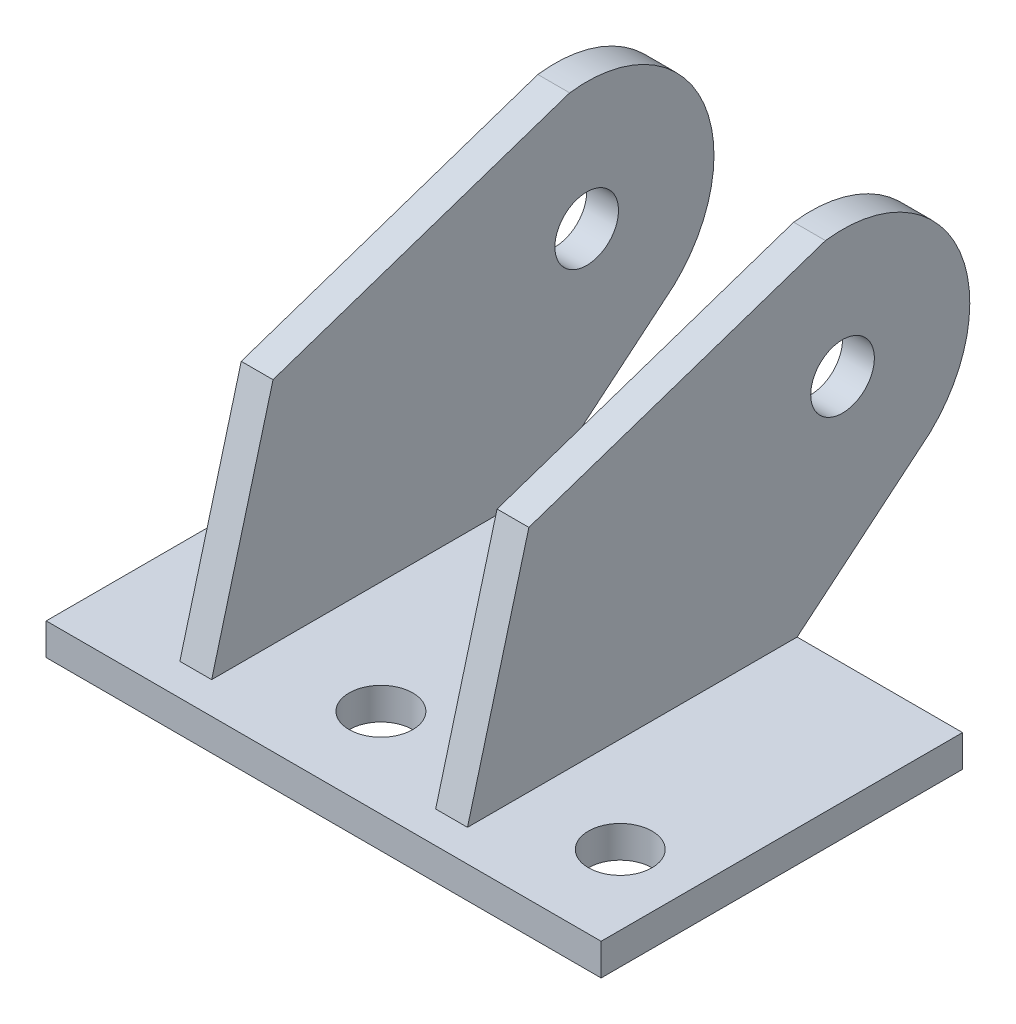
SolidWorks part; units mm, degrees
material "AISI 4130 Steel, annealed at 865C"
ref_plane "Front Plane" through (0, 0, 0) normal (0, 0, 1) x (1, 0, 0)
ref_plane "Top Plane" through (0, 0, 0) normal (0, 1, 0) x (1, 0, 0)
ref_plane "Right Plane" through (0, 0, 0) normal (1, 0, 0) x (0, 0, -1)
sketch "Sketch1" plane through (0, 0, 0) normal (0, 1, 0) x (1, 0, 0)
  line L1 (0, 0) -> (55.372, 0)
  line L2 (0, 0) -> (0, 36.068)
  line L3 (0, 36.068) -> (55.372, 36.068)
  line L4 (55.372, 0) -> (55.372, 36.068)
  line L5 (10.16, 29.718) -> (13.335, 29.718) construction
  line L6 (10.16, 29.718) -> (10.16, 10.414) construction
  line L7 (10.16, 10.414) -> (13.335, 10.414) construction
  line L8 (13.335, 29.718) -> (13.335, 10.414) construction
  line L9 (35.687, 29.718) -> (38.862, 29.718) construction
  line L10 (35.687, 29.718) -> (35.687, 10.414) construction
  line L11 (35.687, 10.414) -> (38.862, 10.414) construction
  line L12 (38.862, 29.718) -> (38.862, 10.414) construction
  circle A0 centre (24.511, 8.89) radius 3.175
  circle A1 centre (24.511, 26.162) radius 3.175
  circle A2 centre (48.387, 8.89) radius 3.175
  dimension "D12" = 6.35
  dimension "D13" = 6.35
  dimension "D14" = 6.35
  dimension "D1" = 55.372
  dimension "D2" = 36.068
  dimension "D3" = 10.16
  dimension "D4" = 6.35
  dimension "D5" = 3.175
  dimension "D6" = 19.304
  dimension "D7" = 22.352
  dimension "D8" = 3.175
  dimension "D9" = 19.304
  dimension "D10" = 11.176
  dimension "D11" = 11.176
  dimension "D15" = 8.89
  dimension "D16" = 17.272
  dimension "D17" = 23.876
extrude "Boss-Extrude1" add sketch "Sketch1" along normal blind 3.175
sketch "Sketch2" plane through (0, 3.175, 0) normal (0, 1, 0) x (1, 0, 0)
  line L0 (0, 0) -> (55.372, 0) construction
  line L1 (10.16, 3.175) -> (13.335, 3.175)
  line L2 (10.16, 3.175) -> (10.16, 53.975)
  line L3 (10.16, 53.975) -> (13.335, 53.975)
  line L4 (13.335, 3.175) -> (13.335, 53.975)
  line L5 (35.687, 3.175) -> (38.862, 3.175)
  line L6 (35.687, 3.175) -> (35.687, 53.975)
  line L7 (35.687, 53.975) -> (38.862, 53.975)
  line L8 (38.862, 3.175) -> (38.862, 53.975)
  circle A1 centre (24.511, 8.89) radius 3.175 construction
  dimension "D5" = 11.176
  dimension "D1" = 22.352
  dimension "D2" = 3.175
  dimension "D3" = 3.175
  dimension "D4" = 50.8
  dimension "D6" = 3.175
extrude "Boss-Extrude2" add sketch "Sketch2" along normal blind 38.1
sketch "Sketch3" plane through (10.16, 0, 0) normal (-1, 0, 0) x (0, 0, 1)
  circle A0 centre (-40.5975, 23.4355) radius 3.175
  dimension "D1" = 6.35
extrude "Cut-Extrude1" cut sketch "Sketch3" against normal up to surface (28.702 mm away) up to face at (38.862, 18.415, -30.0736)
sketch "Sketch4" plane through (10.16, 0, 0) normal (-1, 0, 0) x (0, 0, 1)
  line L0 (-3.175, 3.175) -> (-3.175, 41.275)
  line L1 (-3.175, 41.275) -> (-53.975, 41.275)
  line L2 (-53.975, 41.275) -> (-53.975, 3.175)
  line L3 (-53.975, 3.175) -> (-36.068, 3.175)
  line L4 (-36.068, 3.175) -> (-49.3422, 14.2257)
  line L5 (-3.175, 3.175) -> (-9.3003, 26.035)
  line L6 (-36.068, 3.175) -> (0, 3.175) construction
  line L7 (-9.3003, 26.035) -> (-38.8983, 36.0214)
  arc A0 (-38.8983, 36.0214) -> (-49.3422, 14.2257) centre (-40.5975, 23.4355) ccw
  dimension "D3" = 12.7
  dimension "D1" = 15
  dimension "D2" = 22.86
  dimension "D4" = 17.272
  dimension "D5" = 29.598
extrude "Cut-Extrude2" cut sketch "Sketch4" against normal through all
